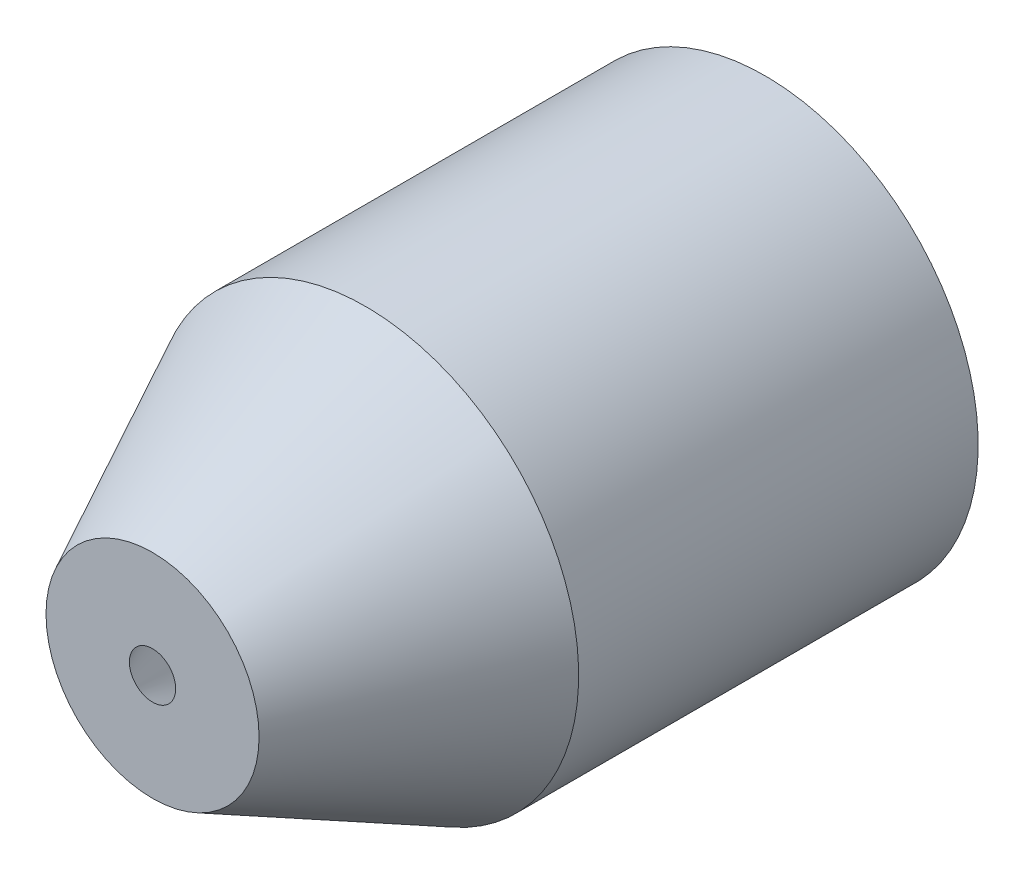
SolidWorks part; units mm, degrees
ref_plane "Front Plane" through (0, 0, 0) normal (0, 0, 1) x (1, 0, 0)
ref_plane "Top Plane" through (0, 0, 0) normal (0, 1, 0) x (1, 0, 0)
ref_plane "Right Plane" through (0, 0, 0) normal (1, 0, 0) x (0, 0, -1)
sketch "Sketch1" plane through (0, 0, 0) normal (0, 1, 0) x (1, 0, 0)
  line L0 (0, 36.046) -> (0, -52.2299) construction
  line L1 (0, 0) -> (-8, 0)
  line L2 (-8, 0) -> (-8, -15)
  line L3 (-8, -15) -> (-4, -23)
  line L4 (-4, -23) -> (0, -23)
  line L5 (0, 0) -> (0, -23)
  dimension "D1" = 8
  dimension "D2" = 15
  dimension "D3" = 8
  dimension "D4" = 4
revolve "Revolve1" add sketch "Sketch1" angle 360 about L0
shell "Shell1" thickness 2.8
sketch "Sketch3" plane through (0, 0, 0) normal (0, 0, -1) x (-1, 0, 0)
  circle A1 centre (0, 0) radius 8
  circle A2 centre (0, 0) radius 8
  dimension "D1" = 0
sketch "Sketch6" plane through (0, 0, 0) normal (0, 0, -1) x (-1, 0, 0)
  circle A0 centre (0, 0) radius 5.1
  dimension "D1" = 10.2
extrude "Cut-Extrude4" cut sketch "Sketch6" against normal blind 15
